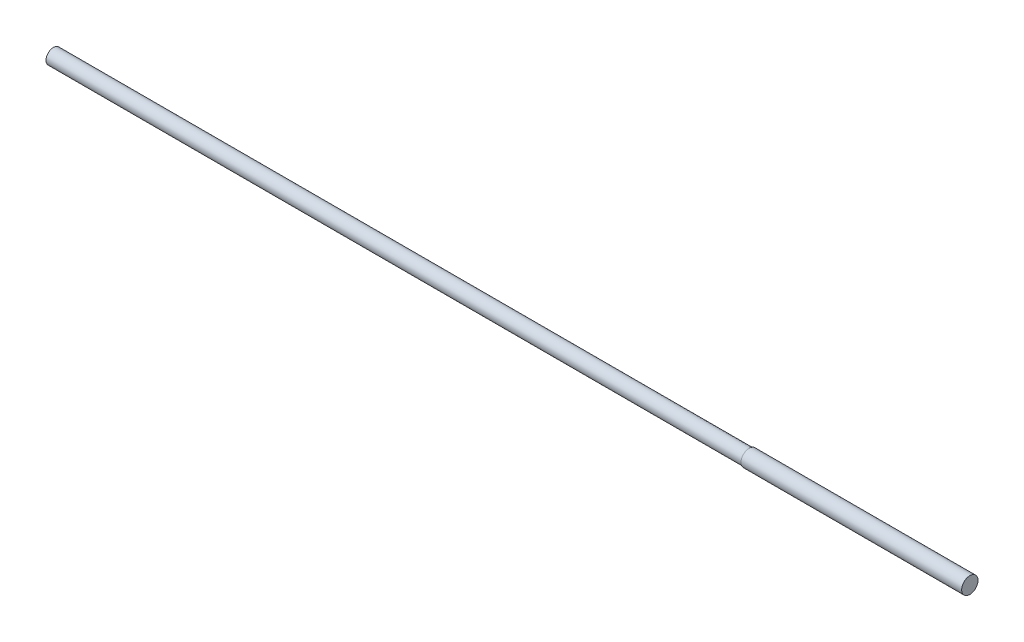
SolidWorks part; units mm, degrees
ref_plane "Piano frontale" through (0, 0, 0) normal (0, 0, 1) x (1, 0, 0)
ref_plane "Piano superiore" through (0, 0, 0) normal (0, 1, 0) x (1, 0, 0)
ref_plane "Piano destro" through (0, 0, 0) normal (1, 0, 0) x (0, 0, -1)
sketch "Schizzo1" plane through (0, 0, 0) normal (1, 0, 0) x (0, 0, -1)
  circle A0 centre (0, 0) radius 0.845
  dimension "D1" = 1.69
extrude "Estrusione-Estrusione1" add sketch "Schizzo1" along normal blind 103.82
sketch "Schizzo2" plane through (103.82, 0, 0) normal (1, 0, 0) x (0, 0, -1)
  circle A0 centre (0, 0) radius 0.925
  dimension "D1" = 1.85
extrude "Estrusione-Estrusione2" add sketch "Schizzo2" against normal blind 25
cosmetic thread "Filettatura cosmetica1" parameters "D2"=1.69
